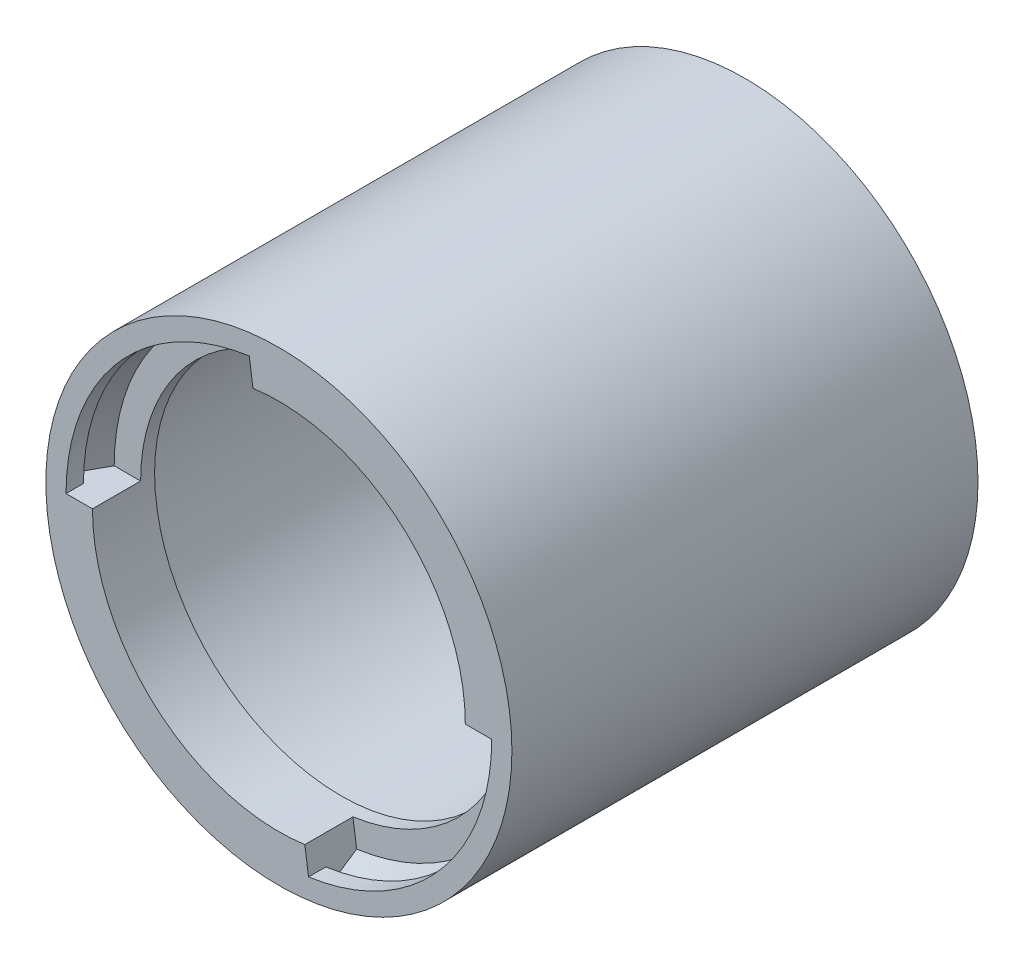
SolidWorks part; units mm, degrees
ref_plane "Ön Düzlem" through (0, 0, 0) normal (0, 0, 1) x (1, 0, 0)
ref_plane "Üst Düzlem" through (0, 0, 0) normal (0, 1, 0) x (1, 0, 0)
ref_plane "Sağ Düzlem" through (0, 0, 0) normal (1, 0, 0) x (0, 0, -1)
sketch "Çizim1" plane through (0, 0, 0) normal (0, 0, 1) x (1, 0, 0)
  circle A0 centre (0, 0) radius 15
  circle A1 centre (0, 0) radius 13.5
  dimension "D1" = 30
  dimension "D2" = 27
extrude "Yükseklik-Ekstrüzyon1" add sketch "Çizim1" along normal blind 30
sketch "Çizim3" plane through (0, 0, 30) normal (0, 0, 1) x (1, 0, 0)
  circle A0 centre (0, 0) radius 13.5 construction
  circle A1 centre (0, 0) radius 13.5
  circle A2 centre (0, 0) radius 12
  dimension "D1" = 24
extrude "Yükseklik-Ekstrüzyon2" add sketch "Çizim3" against normal blind 4
sketch "Çizim4" plane through (0, 0, 0) normal (0, 1, 0) x (1, 0, 0)
  line L0 (-13.7, -30) -> (-13.7, -28.88)
  line L1 (-13.7, -28.88) -> (-14.43, -28.23)
  line L2 (-14.43, -28.23) -> (-13.7, -26.9)
  line L3 (-13.7, -26.9) -> (-11.7, -26.9)
  line L4 (-11.7, -26.9) -> (-11.7, -30)
  line L5 (-11.7, -30) -> (-13.7, -30)
  line L7 (-15, -30) -> (15, -30) construction
  point P9 (0, 0)
  dimension "D1" = 1.3
  dimension "D2" = 2
  dimension "D3" = 2
  dimension "D4" = 3.1
  dimension "D5" = 0.73
  dimension "D6" = 0.65
  dimension "D7" = 1.12
sketch "Çizim5" plane through (0, 0, 30) normal (0, 0, 1) x (1, 0, 0)
  line L0 (0, 0) -> (-13.7, 0) construction
  line L1 (0, 0) -> (-1.9067, 13.5667) construction
  arc A0 (-1.9067, 13.5667) -> (-13.7, 0) centre (0, 0) ccw
  dimension "D1" = 27.4
  dimension "D2" = 82
sweep "Kes-Süpür2" cut profiles "Çizim4" path "Çizim5"
sketch "Çizim7" plane through (0, 0, 30) normal (0, 0, 1) x (1, 0, 0)
  line L0 (0, 0) -> (-9.0565, 7.8727) construction
  line L1 (0, 0) -> (7.8727, 9.0565)
  arc A0 (-1.6701, 11.8832) -> (-12, 0) centre (0, 0) ccw construction
  arc A1 (-12, 0) -> (-1.6701, 11.8832) centre (0, 0) ccw construction
  dimension "D1" = 90
ref_plane "Düzlem2" through (0, 0, 0) normal (0.7547, -0.6561, 0) x (0.6561, 0.7547, 0)
mirror "Aynalama2" about plane through (0, 0, 0) normal (0.7547, -0.6561, 0) of "Kes-Süpür2"
